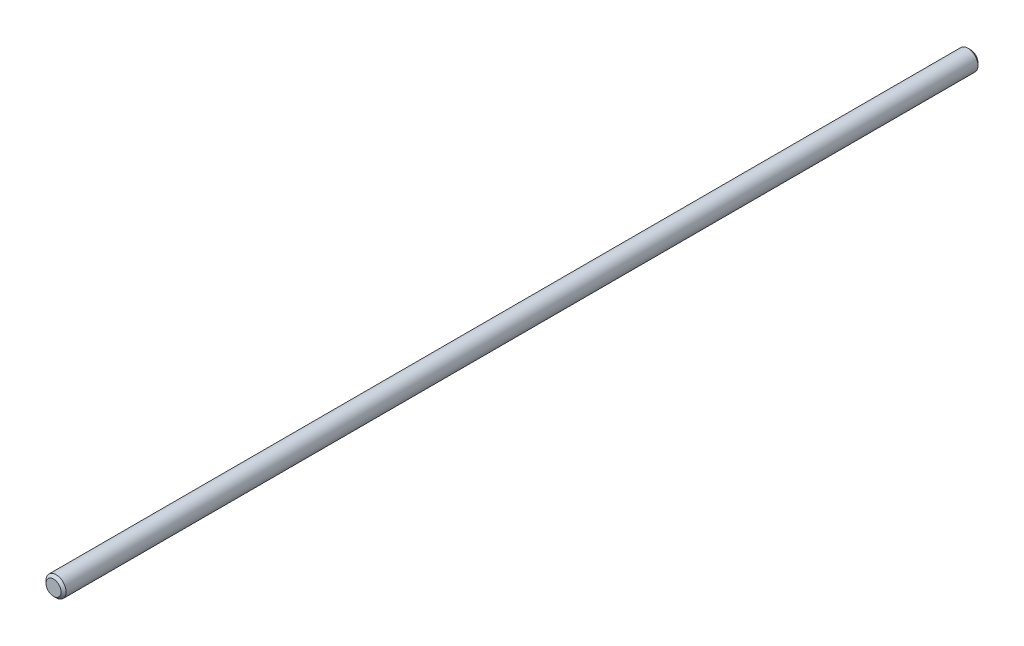
SolidWorks part; units mm, degrees
ref_plane "Piano frontale" through (0, 0, 0) normal (0, 0, 1) x (1, 0, 0)
ref_plane "Piano superiore" through (0, 0, 0) normal (0, 1, 0) x (1, 0, 0)
ref_plane "Piano destro" through (0, 0, 0) normal (1, 0, 0) x (0, 0, -1)
sketch "Schizzo1" plane through (0, 0, 0) normal (0, 0, 1) x (1, 0, 0)
  circle A0 centre (0, 0) radius 4
  dimension "D1" = 8
extrude "Estrusione-Estrusione1" add sketch "Schizzo1" along normal blind 365
chamfer "Smusso1" distance 1 angle 45 2 edges at (4, 0, 0) (4, 0, 365)
sketch "Schizzo2" plane through (0, 0, 0) normal (0, 1, 0) x (1, 0, 0)
  line L0 (4, -1) -> (4, -364) construction
